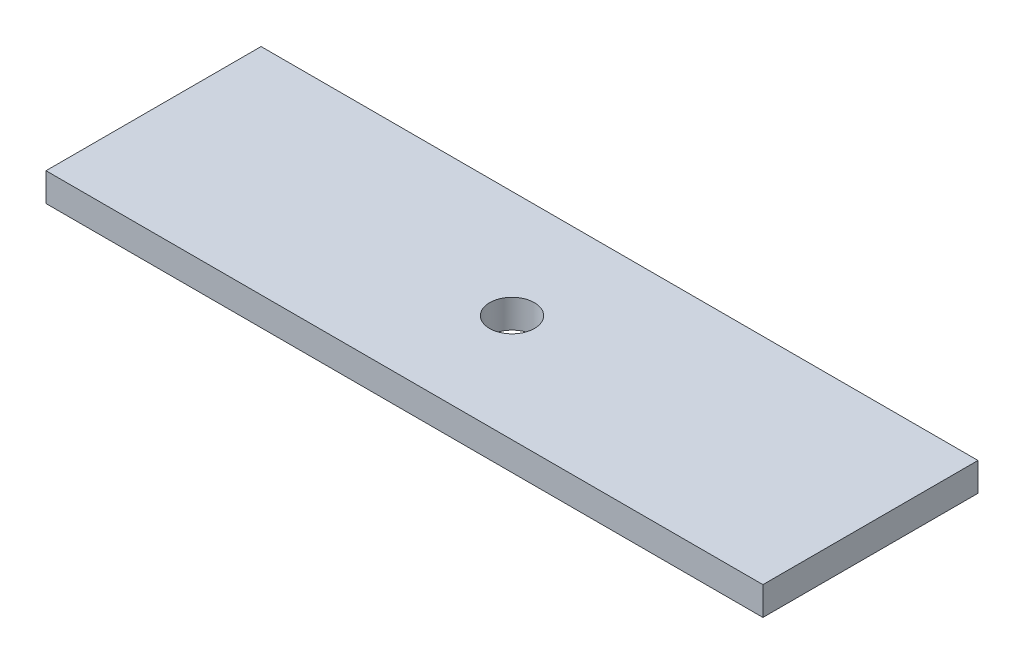
SolidWorks part; units mm, degrees
ref_plane "Front" through (0, 0, 0) normal (0, 0, 1) x (1, 0, 0)
ref_plane "Top" through (0, 0, 0) normal (0, 1, 0) x (1, 0, 0)
ref_plane "Right" through (0, 0, 0) normal (1, 0, 0) x (0, 0, -1)
sketch "Sketch1" plane through (0, 0, 0) normal (0, 1, 0) x (1, 0, 0)
  line L1 (-20, 6) -> (20, 6)
  line L2 (-20, 6) -> (-20, -6)
  line L3 (-20, -6) -> (20, -6)
  line L4 (20, 6) -> (20, -6)
  line L5 (-20, 6) -> (20, -6) construction
  line L6 (-20, -6) -> (20, 6) construction
  circle A0 centre (0, 0) radius 1.25
  point P0 (0, 0)
  dimension "D3" = 2.5
  dimension "D1" = 12
  dimension "D2" = 40
extrude "Boss-Extrude1" add sketch "Sketch1" along normal blind 1.5875
